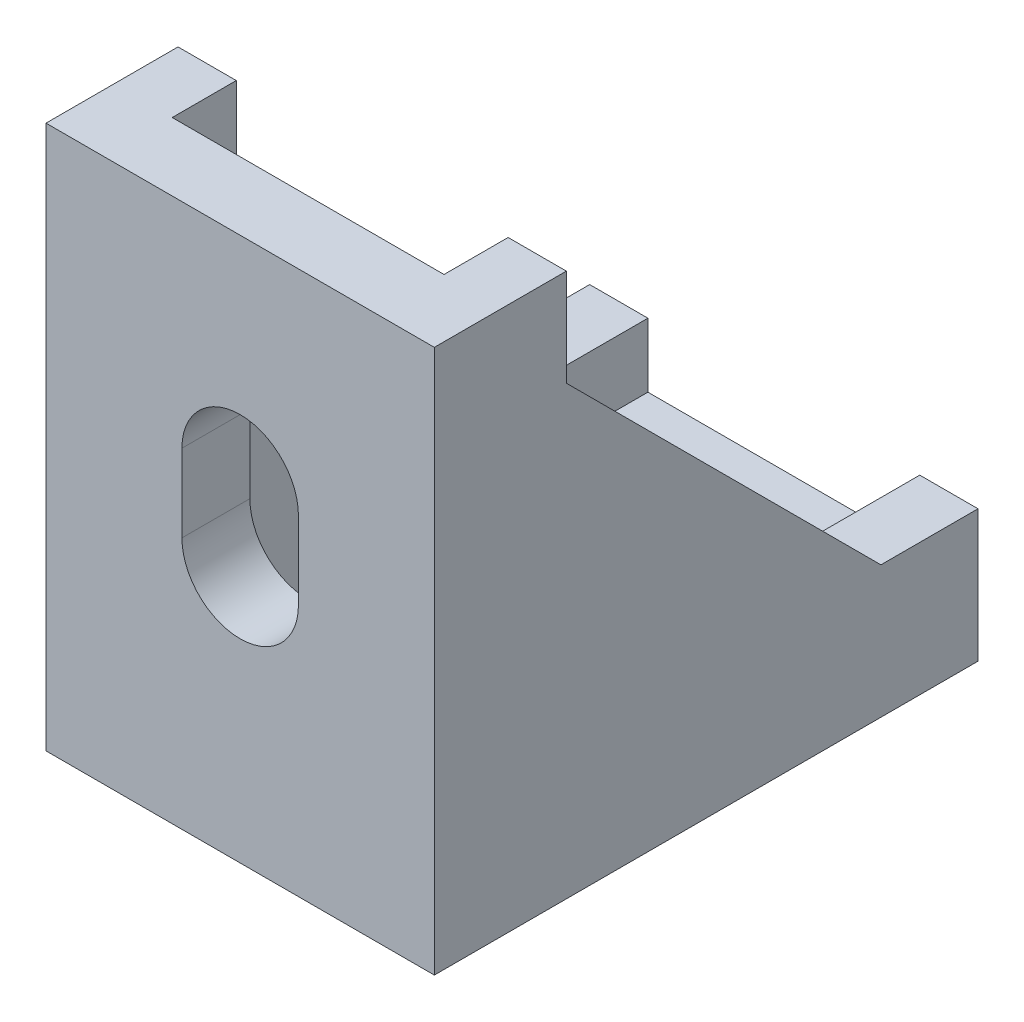
SolidWorks part; units mm, degrees
other "Camera1"
material "201.0-T6 Insulated Mold Casting (SS)"
ref_plane "Front Plane" through (0, 0, 0) normal (0, 0, 1) x (1, 0, 0)
ref_plane "Top Plane" through (0, 0, 0) normal (0, 1, 0) x (1, 0, 0)
ref_plane "Right Plane" through (0, 0, 0) normal (1, 0, 0) x (0, 0, -1)
sketch "Sketch2" plane through (0, 0, 0) normal (0, 1, 0) x (1, 0, 0)
  line L0 (0, -1) -> (0, 3) construction
  line L1 (10, -14) -> (-10, -14)
  line L2 (10, -14) -> (10, 14)
  line L3 (10, 14) -> (-10, 14)
  line L4 (-10, -14) -> (-10, 14)
  line L5 (10, -14) -> (-10, 14) construction
  line L6 (10, 14) -> (-10, -14) construction
  line L7 (-3, -1) -> (-3, 3)
  line L8 (3, -1) -> (3, 3)
  arc A0 (-3, -1) -> (3, -1) centre (0, -1) ccw
  arc A1 (3, 3) -> (-3, 3) centre (0, 3) ccw
  point P0 (0, 0)
  point P8 (0, 1)
  dimension "D5" = 3
  dimension "D1" = 20
  dimension "D2" = 28
  dimension "D3" = 13
  dimension "D4" = 4
extrude "Boss-Extrude1" add sketch "Sketch2" along normal blind 3.5 contours L8 A1 L7 A0 | L2 L3 L4 L1
sketch "Sketch3" plane through (0, 0, 14) normal (0, 0, 1) x (1, 0, 0)
  line L0 (0, 17) -> (0, 13) construction
  line L1 (-10, 0) -> (10, 0)
  line L2 (-10, 0) -> (-10, 28)
  line L3 (-10, 28) -> (10, 28)
  line L4 (10, 0) -> (10, 28)
  line L5 (3, 17) -> (3, 13)
  line L6 (-3, 17) -> (-3, 13)
  arc A0 (3, 17) -> (-3, 17) centre (0, 17) ccw
  arc A1 (-3, 13) -> (3, 13) centre (0, 13) ccw
  point P8 (0, 15)
  dimension "D5" = 3
  dimension "D1" = 20
  dimension "D2" = 28
  dimension "D3" = 4
  dimension "D4" = 13
extrude "Boss-Extrude2" add sketch "Sketch3" against normal blind 3.5
sketch "Sketch4" plane through (10, 0, 0) normal (1, 0, 0) x (0, 0, -1)
  line L0 (-14, 0) -> (14, 0) construction
  line L1 (-14, 28) -> (-14, 0) construction
  line L2 (-14, 0) -> (14, 0)
  line L3 (-14, 28) -> (-14, 0)
  line L4 (-14, 28) -> (-7.2, 28)
  line L5 (-7.2, 28) -> (-7.2, 23)
  line L6 (14, 0) -> (14, 6.8)
  line L7 (14, 6.8) -> (9, 6.8)
  line L8 (9, 6.8) -> (-7.2, 23)
  dimension "D1" = 6.8
  dimension "D2" = 5
extrude "Boss-Extrude3" add sketch "Sketch4" against normal blind 3
sketch "Sketch5" plane through (-10, 0, 0) normal (-1, 0, 0) x (0, 0, 1)
  line L7 (-14, 0) -> (14, 0)
  line L8 (-14, 6.8) -> (-14, 0)
  line L9 (-9, 6.8) -> (-14, 6.8)
  line L10 (7.2, 23) -> (-9, 6.8)
  line L11 (7.2, 28) -> (7.2, 23)
  line L12 (14, 28) -> (7.2, 28)
  line L13 (14, 0) -> (14, 28)
  line L14 (-14, 0) -> (14, 0)
  line L15 (-14, 6.8) -> (-14, 0)
  line L16 (-9, 6.8) -> (-14, 6.8)
  line L17 (7.2, 23) -> (-9, 6.8)
  line L18 (7.2, 28) -> (7.2, 23)
  line L19 (14, 28) -> (7.2, 28)
  line L20 (14, 0) -> (14, 28)
  dimension "D1" = 0
extrude "Boss-Extrude4" add sketch "Sketch5" against normal blind 3
